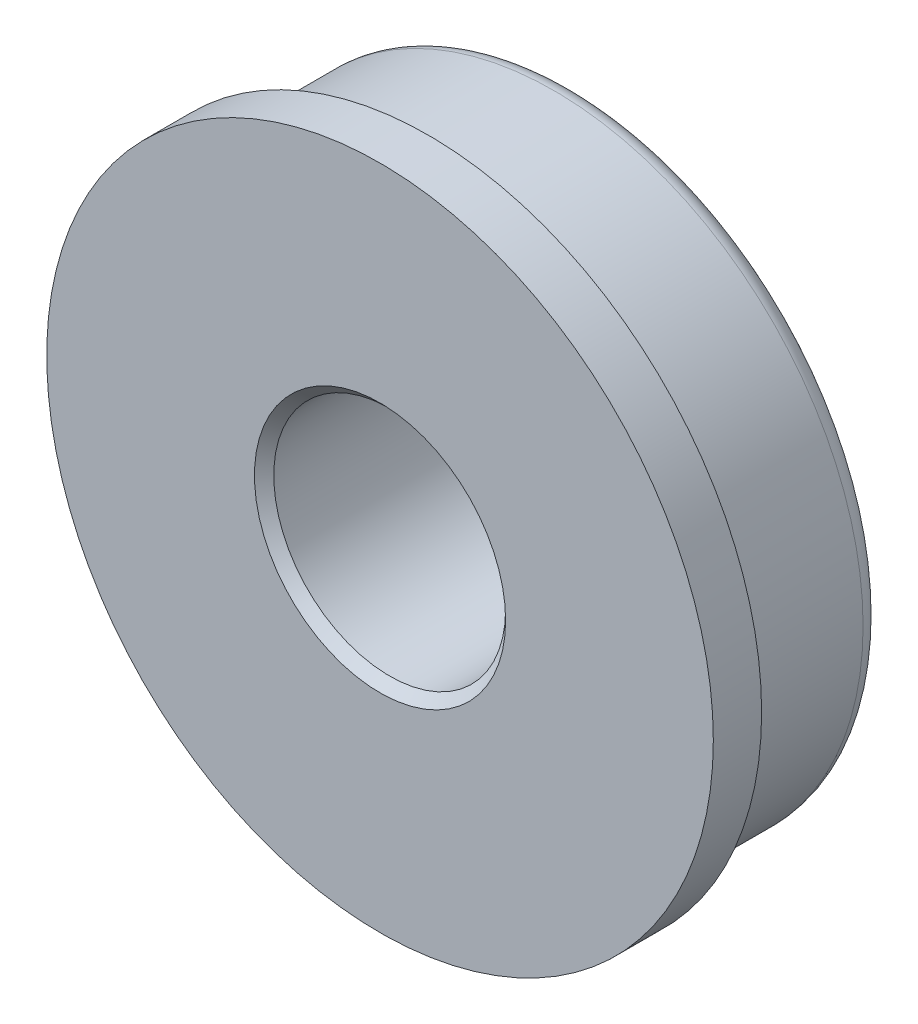
SolidWorks part; units mm, degrees
ref_plane "前视基准面" through (0, 0, 0) normal (0, 0, 1) x (1, 0, 0)
ref_plane "上视基准面" through (0, 0, 0) normal (0, 1, 0) x (1, 0, 0)
ref_plane "右视基准面" through (0, 0, 0) normal (1, 0, 0) x (0, 0, -1)
sketch "草图1" plane through (0, 0, 0) normal (0, 0, 1) x (1, 0, 0)
  circle A0 centre (0, 0) radius 16
  circle A1 centre (0, 0) radius 6
  dimension "D1" = 12
  dimension "D2" = 32
extrude "凸台-拉伸1" add sketch "草图1" along normal mid plane 10
sketch "草图2" plane through (0, 0, 5) normal (0, 0, 1) x (1, 0, 0)
  circle A0 centre (0, 0) radius 17.25
  circle A1 centre (0, 0) radius 16 construction
  circle A2 centre (0, 0) radius 16
  dimension "D1" = 34.5
extrude "凸台-拉伸2" add sketch "草图2" against normal blind 2.5
chamfer "倒角1" distance 0.5 angle 45 2 edges at (6, 0, -5) (6, 0, 5)
fillet "圆角1" radius 1 1 edges at (16, 0, -5)
